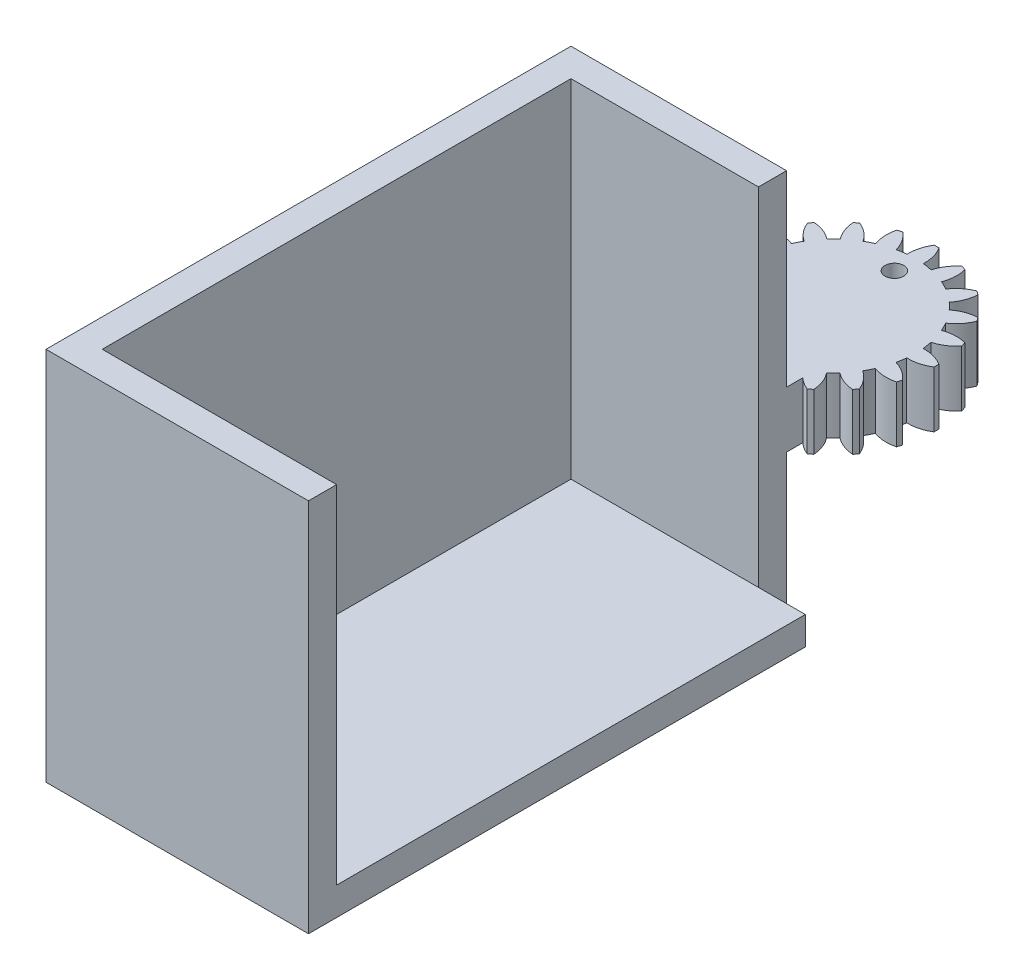
SolidWorks part; units mm, degrees
ref_plane "前视基准面" through (0, 0, 0) normal (0, 0, 1) x (1, 0, 0)
ref_plane "上视基准面" through (0, 0, 0) normal (0, 1, 0) x (1, 0, 0)
ref_plane "右视基准面" through (0, 0, 0) normal (1, 0, 0) x (0, 0, -1)
sketch "草图1" plane through (0, 0, 0) normal (0, 1, 0) x (1, 0, 0)
  line L0 (-5, 0) -> (5, 0) construction
  line L1 (5, 0) -> (5, -13)
  line L2 (-5, 0) -> (-5, -10)
  line L3 (-5, -10) -> (-18, -10)
  line L4 (-18, -10) -> (-18, -66)
  line L5 (-18, -66) -> (10, -66)
  line L6 (10, -66) -> (10, -63)
  line L7 (10, -63) -> (-15, -63)
  line L8 (-15, -63) -> (-15, -13)
  line L9 (-15, -13) -> (5, -13)
  arc A0 (5, 0) -> (-5, 0) centre (0, 0) ccw
  arc A1 (-5, 0) -> (5, 0) centre (0, 0) ccw construction
  dimension "D1" = 10
  dimension "D2" = 3
  dimension "D3" = 3
  dimension "D4" = 3
  dimension "D5" = 10
  dimension "D6" = 10
  dimension "D7" = 25
  dimension "D8" = 50
extrude "凸台-拉伸1" add sketch "草图1" against normal blind 6
sketch "草图2" plane through (0, 0, 0) normal (0, 1, 0) x (1, 0, 0)
  line L0 (-15, -13) -> (5, -13) construction
  line L1 (-15, -63) -> (-15, -13) construction
  line L2 (10, -63) -> (-15, -63) construction
  line L3 (10, -66) -> (10, -63) construction
  line L4 (-18, -66) -> (10, -66) construction
  line L5 (-18, -10) -> (-18, -66) construction
  line L6 (-15, -13) -> (5, -13)
  line L7 (-15, -63) -> (-15, -13)
  line L8 (10, -63) -> (-15, -63)
  line L9 (10, -66) -> (10, -63)
  line L10 (-18, -66) -> (10, -66)
  line L11 (-18, -10) -> (-18, -66)
  line L12 (-18, -10) -> (5, -10)
  line L13 (5, -13) -> (5, 0) construction
  line L14 (5, -10) -> (5, -13)
extrude "凸台-拉伸2" add sketch "草图2" along normal mid plane 40
sketch "草图3" plane through (0, -20, 0) normal (0, -1, 0) x (1, 0, 0)
  line L1 (-15, 13) -> (10, 13)
  line L2 (-15, 13) -> (-15, 63)
  line L3 (-15, 63) -> (10, 63)
  line L4 (10, 13) -> (10, 63)
extrude "凸台-拉伸3" add sketch "草图3" against normal blind 3
sketch "草图4" plane through (0, -6, 0) normal (0, -1, 0) x (1, 0, 0)
  arc A80 (0.8607, 8.7066) -> (0.2434, 10.9973) centre (-3.1365, 8.858) ccw
  arc A81 (0.2434, 10.9973) -> (-0.2736, 10.9966) centre (0, 0) ccw
  arc A82 (-0.2736, 10.9966) -> (-0.8846, 8.7042) centre (3.1121, 8.8666) ccw
  arc A83 (-0.8846, 8.7042) -> (-1.8719, 8.5464) centre (0, 0) ccw
  arc A84 (-1.8719, 8.5464) -> (-3.1668, 10.5343) centre (-5.7202, 7.4553) ccw
  arc A85 (-3.1668, 10.5343) -> (-3.6584, 10.3738) centre (0, 0) ccw
  arc A86 (-3.6584, 10.3738) -> (-3.531, 8.0048) centre (0.2198, 9.3944) ccw
  arc A87 (-3.531, 8.0048) -> (-4.4213, 7.5497) centre (0, 0) ccw
  arc A88 (-4.4213, 7.5497) -> (-6.2671, 9.0401) centre (-7.7441, 5.3227) ccw
  arc A89 (-6.2671, 9.0401) -> (-6.685, 8.7356) centre (0, 0) ccw
  arc A90 (-6.685, 8.7356) -> (-5.8318, 6.5219) centre (-2.6939, 9.0025) ccw
  arc A91 (-5.8318, 6.5219) -> (-6.5379, 5.8139) centre (0, 0) ccw
  arc A92 (-6.5379, 5.8139) -> (-8.7539, 6.661) centre (-9.0099, 2.6692) ccw
  arc A93 (-8.7539, 6.661) -> (-9.0573, 6.2423) centre (0, 0) ccw
  arc A94 (-9.0573, 6.2423) -> (-7.5618, 4.4005) centre (-5.344, 7.7294) ccw
  arc A95 (-7.5618, 4.4005) -> (-8.0145, 3.509) centre (0, 0) ccw
  arc A96 (-8.0145, 3.509) -> (-10.3838, 3.6299) centre (-9.3937, -0.2457) ccw
  arc A97 (-10.3838, 3.6299) -> (-10.5429, 3.1379) centre (0, 0) ccw
  arc A98 (-10.5429, 3.1379) -> (-8.5515, 1.8484) centre (-7.471, 5.6997) ccw
  arc A99 (-8.5515, 1.8484) -> (-8.7066, 0.8607) centre (0, 0) ccw
  arc A100 (-8.7066, 0.8607) -> (-10.9973, 0.2434) centre (-8.858, -3.1365) ccw
  arc A101 (-10.9973, 0.2434) -> (-10.9966, -0.2736) centre (0, 0) ccw
  arc A102 (-10.9966, -0.2736) -> (-8.7042, -0.8846) centre (-8.8666, 3.1121) ccw
  arc A103 (-8.7042, -0.8846) -> (-8.5464, -1.8719) centre (0, 0) ccw
  arc A104 (-8.5464, -1.8719) -> (-10.5343, -3.1668) centre (-7.4553, -5.7202) ccw
  arc A105 (-10.5343, -3.1668) -> (-10.3738, -3.6584) centre (0, 0) ccw
  arc A106 (-10.3738, -3.6584) -> (-8.0048, -3.531) centre (-9.3944, 0.2198) ccw
  arc A107 (-8.0048, -3.531) -> (-7.5497, -4.4213) centre (0, 0) ccw
  arc A108 (-7.5497, -4.4213) -> (-9.0401, -6.2671) centre (-5.3227, -7.7441) ccw
  arc A109 (-9.0401, -6.2671) -> (-8.7356, -6.685) centre (0, 0) ccw
  arc A110 (-8.7356, -6.685) -> (-6.5219, -5.8318) centre (-9.0025, -2.6939) ccw
  arc A111 (-6.5219, -5.8318) -> (-5.8139, -6.5379) centre (0, 0) ccw
  arc A112 (-5.8139, -6.5379) -> (-6.661, -8.7539) centre (-2.6692, -9.0099) ccw
  arc A113 (-6.661, -8.7539) -> (-6.2423, -9.0573) centre (0, 0) ccw
  arc A114 (-6.2423, -9.0573) -> (-4.4005, -7.5618) centre (-7.7294, -5.344) ccw
  arc A115 (-4.4005, -7.5618) -> (-3.509, -8.0145) centre (0, 0) ccw
  arc A116 (-3.509, -8.0145) -> (-3.6299, -10.3838) centre (0.2457, -9.3937) ccw
  arc A117 (-3.6299, -10.3838) -> (-3.1379, -10.5429) centre (0, 0) ccw
  arc A118 (-3.1379, -10.5429) -> (-1.8484, -8.5515) centre (-5.6997, -7.471) ccw
  arc A119 (-1.8484, -8.5515) -> (-0.8607, -8.7066) centre (0, 0) ccw
  arc A120 (-0.8607, -8.7066) -> (-0.2434, -10.9973) centre (3.1365, -8.858) ccw
  arc A121 (-0.2434, -10.9973) -> (0.2736, -10.9966) centre (0, 0) ccw
  arc A122 (0.2736, -10.9966) -> (0.8846, -8.7042) centre (-3.1121, -8.8666) ccw
  arc A123 (0.8846, -8.7042) -> (1.8719, -8.5464) centre (0, 0) ccw
  arc A124 (1.8719, -8.5464) -> (3.1668, -10.5343) centre (5.7202, -7.4553) ccw
  arc A125 (3.1668, -10.5343) -> (3.6584, -10.3738) centre (0, 0) ccw
  arc A126 (3.6584, -10.3738) -> (3.531, -8.0048) centre (-0.2198, -9.3944) ccw
  arc A127 (3.531, -8.0048) -> (4.4213, -7.5497) centre (0, 0) ccw
  arc A128 (4.4213, -7.5497) -> (6.2671, -9.0401) centre (7.7441, -5.3227) ccw
  arc A129 (6.2671, -9.0401) -> (6.685, -8.7356) centre (0, 0) ccw
  arc A130 (6.685, -8.7356) -> (5.8318, -6.5219) centre (2.6939, -9.0025) ccw
  arc A131 (5.8318, -6.5219) -> (6.5379, -5.8139) centre (0, 0) ccw
  arc A132 (6.5379, -5.8139) -> (8.7539, -6.661) centre (9.0099, -2.6692) ccw
  arc A133 (8.7539, -6.661) -> (9.0573, -6.2423) centre (0, 0) ccw
  arc A134 (9.0573, -6.2423) -> (7.5618, -4.4005) centre (5.344, -7.7294) ccw
  arc A135 (7.5618, -4.4005) -> (8.0145, -3.509) centre (0, 0) ccw
  arc A136 (8.0145, -3.509) -> (10.3838, -3.6299) centre (9.3937, 0.2457) ccw
  arc A137 (10.3838, -3.6299) -> (10.5429, -3.1379) centre (0, 0) ccw
  arc A138 (10.5429, -3.1379) -> (8.5515, -1.8484) centre (7.471, -5.6997) ccw
  arc A139 (8.5515, -1.8484) -> (8.7066, -0.8607) centre (0, 0) ccw
  arc A140 (8.7066, -0.8607) -> (10.9973, -0.2434) centre (8.858, 3.1365) ccw
  arc A141 (10.9973, -0.2434) -> (10.9966, 0.2736) centre (0, 0) ccw
  arc A142 (10.9966, 0.2736) -> (8.7042, 0.8846) centre (8.8666, -3.1121) ccw
  arc A143 (8.7042, 0.8846) -> (8.5464, 1.8719) centre (0, 0) ccw
  arc A144 (8.5464, 1.8719) -> (10.5343, 3.1668) centre (7.4553, 5.7202) ccw
  arc A145 (10.5343, 3.1668) -> (10.3738, 3.6584) centre (0, 0) ccw
  arc A146 (10.3738, 3.6584) -> (8.0048, 3.531) centre (9.3944, -0.2198) ccw
  arc A147 (8.0048, 3.531) -> (7.5497, 4.4213) centre (0, 0) ccw
  arc A148 (7.5497, 4.4213) -> (9.0401, 6.2671) centre (5.3227, 7.7441) ccw
  arc A149 (9.0401, 6.2671) -> (8.7356, 6.685) centre (0, 0) ccw
  arc A150 (8.7356, 6.685) -> (6.5219, 5.8318) centre (9.0025, 2.6939) ccw
  arc A151 (6.5219, 5.8318) -> (5.8139, 6.5379) centre (0, 0) ccw
  arc A152 (5.8139, 6.5379) -> (6.661, 8.7539) centre (2.6692, 9.0099) ccw
  arc A153 (6.661, 8.7539) -> (6.2423, 9.0573) centre (0, 0) ccw
  arc A154 (6.2423, 9.0573) -> (4.4005, 7.5618) centre (7.7294, 5.344) ccw
  arc A155 (4.4005, 7.5618) -> (3.509, 8.0145) centre (0, 0) ccw
  arc A156 (3.509, 8.0145) -> (3.6299, 10.3838) centre (-0.2457, 9.3937) ccw
  arc A157 (3.6299, 10.3838) -> (3.1379, 10.5429) centre (0, 0) ccw
  arc A158 (3.1379, 10.5429) -> (1.8484, 8.5515) centre (5.6997, 7.471) ccw
  arc A159 (1.8484, 8.5515) -> (0.8607, 8.7066) centre (0, 0) ccw
  arc A160 (0.8607, 8.7066) -> (0.2434, 10.9973) centre (-3.1365, 8.858) ccw
  arc A161 (0.2434, 10.9973) -> (-0.2736, 10.9966) centre (0, 0) ccw
  arc A162 (-0.2736, 10.9966) -> (-0.8846, 8.7042) centre (3.1121, 8.8666) ccw
  arc A163 (-0.8846, 8.7042) -> (-1.8719, 8.5464) centre (0, 0) ccw
  arc A164 (-1.8719, 8.5464) -> (-3.1668, 10.5343) centre (-5.7202, 7.4553) ccw
  arc A165 (-3.1668, 10.5343) -> (-3.6584, 10.3738) centre (0, 0) ccw
  arc A166 (-3.6584, 10.3738) -> (-3.531, 8.0048) centre (0.2198, 9.3944) ccw
  arc A167 (-3.531, 8.0048) -> (-4.4213, 7.5497) centre (0, 0) ccw
  arc A168 (-4.4213, 7.5497) -> (-6.2671, 9.0401) centre (-7.7441, 5.3227) ccw
  arc A169 (-6.2671, 9.0401) -> (-6.685, 8.7356) centre (0, 0) ccw
  arc A170 (-6.685, 8.7356) -> (-5.8318, 6.5219) centre (-2.6939, 9.0025) ccw
  arc A171 (-5.8318, 6.5219) -> (-6.5379, 5.8139) centre (0, 0) ccw
  arc A172 (-6.5379, 5.8139) -> (-8.7539, 6.661) centre (-9.0099, 2.6692) ccw
  arc A173 (-8.7539, 6.661) -> (-9.0573, 6.2423) centre (0, 0) ccw
  arc A174 (-9.0573, 6.2423) -> (-7.5618, 4.4005) centre (-5.344, 7.7294) ccw
  arc A175 (-7.5618, 4.4005) -> (-8.0145, 3.509) centre (0, 0) ccw
  arc A176 (-8.0145, 3.509) -> (-10.3838, 3.6299) centre (-9.3937, -0.2457) ccw
  arc A177 (-10.3838, 3.6299) -> (-10.5429, 3.1379) centre (0, 0) ccw
  arc A178 (-10.5429, 3.1379) -> (-8.5515, 1.8484) centre (-7.471, 5.6997) ccw
  arc A179 (-8.5515, 1.8484) -> (-8.7066, 0.8607) centre (0, 0) ccw
  arc A180 (-8.7066, 0.8607) -> (-10.9973, 0.2434) centre (-8.858, -3.1365) ccw
  arc A181 (-10.9973, 0.2434) -> (-10.9966, -0.2736) centre (0, 0) ccw
  arc A182 (-10.9966, -0.2736) -> (-8.7042, -0.8846) centre (-8.8666, 3.1121) ccw
  arc A183 (-8.7042, -0.8846) -> (-8.5464, -1.8719) centre (0, 0) ccw
  arc A184 (-8.5464, -1.8719) -> (-10.5343, -3.1668) centre (-7.4553, -5.7202) ccw
  arc A185 (-10.5343, -3.1668) -> (-10.3738, -3.6584) centre (0, 0) ccw
  arc A186 (-10.3738, -3.6584) -> (-8.0048, -3.531) centre (-9.3944, 0.2198) ccw
  arc A187 (-8.0048, -3.531) -> (-7.5497, -4.4213) centre (0, 0) ccw
  arc A188 (-7.5497, -4.4213) -> (-9.0401, -6.2671) centre (-5.3227, -7.7441) ccw
  arc A189 (-9.0401, -6.2671) -> (-8.7356, -6.685) centre (0, 0) ccw
  arc A190 (-8.7356, -6.685) -> (-6.5219, -5.8318) centre (-9.0025, -2.6939) ccw
  arc A191 (-6.5219, -5.8318) -> (-5.8139, -6.5379) centre (0, 0) ccw
  arc A192 (-5.8139, -6.5379) -> (-6.661, -8.7539) centre (-2.6692, -9.0099) ccw
  arc A193 (-6.661, -8.7539) -> (-6.2423, -9.0573) centre (0, 0) ccw
  arc A194 (-6.2423, -9.0573) -> (-4.4005, -7.5618) centre (-7.7294, -5.344) ccw
  arc A195 (-4.4005, -7.5618) -> (-3.509, -8.0145) centre (0, 0) ccw
  arc A196 (-3.509, -8.0145) -> (-3.6299, -10.3838) centre (0.2457, -9.3937) ccw
  arc A197 (-3.6299, -10.3838) -> (-3.1379, -10.5429) centre (0, 0) ccw
  arc A198 (-3.1379, -10.5429) -> (-1.8484, -8.5515) centre (-5.6997, -7.471) ccw
  arc A199 (-1.8484, -8.5515) -> (-0.8607, -8.7066) centre (0, 0) ccw
  arc A200 (-0.8607, -8.7066) -> (-0.2434, -10.9973) centre (3.1365, -8.858) ccw
  arc A201 (-0.2434, -10.9973) -> (0.2736, -10.9966) centre (0, 0) ccw
  arc A202 (0.2736, -10.9966) -> (0.8846, -8.7042) centre (-3.1121, -8.8666) ccw
  arc A203 (0.8846, -8.7042) -> (1.8719, -8.5464) centre (0, 0) ccw
  arc A204 (1.8719, -8.5464) -> (3.1668, -10.5343) centre (5.7202, -7.4553) ccw
  arc A205 (3.1668, -10.5343) -> (3.6584, -10.3738) centre (0, 0) ccw
  arc A206 (3.6584, -10.3738) -> (3.531, -8.0048) centre (-0.2198, -9.3944) ccw
  arc A207 (3.531, -8.0048) -> (4.4213, -7.5497) centre (0, 0) ccw
  arc A208 (4.4213, -7.5497) -> (6.2671, -9.0401) centre (7.7441, -5.3227) ccw
  arc A209 (6.2671, -9.0401) -> (6.685, -8.7356) centre (0, 0) ccw
  arc A210 (6.685, -8.7356) -> (5.8318, -6.5219) centre (2.6939, -9.0025) ccw
  arc A211 (5.8318, -6.5219) -> (6.5379, -5.8139) centre (0, 0) ccw
  arc A212 (6.5379, -5.8139) -> (8.7539, -6.661) centre (9.0099, -2.6692) ccw
  arc A213 (8.7539, -6.661) -> (9.0573, -6.2423) centre (0, 0) ccw
  arc A214 (9.0573, -6.2423) -> (7.5618, -4.4005) centre (5.344, -7.7294) ccw
  arc A215 (7.5618, -4.4005) -> (8.0145, -3.509) centre (0, 0) ccw
  arc A216 (8.0145, -3.509) -> (10.3838, -3.6299) centre (9.3937, 0.2457) ccw
  arc A217 (10.3838, -3.6299) -> (10.5429, -3.1379) centre (0, 0) ccw
  arc A218 (10.5429, -3.1379) -> (8.5515, -1.8484) centre (7.471, -5.6997) ccw
  arc A219 (8.5515, -1.8484) -> (8.7066, -0.8607) centre (0, 0) ccw
  arc A220 (8.7066, -0.8607) -> (10.9973, -0.2434) centre (8.858, 3.1365) ccw
  arc A221 (10.9973, -0.2434) -> (10.9966, 0.2736) centre (0, 0) ccw
  arc A222 (10.9966, 0.2736) -> (8.7042, 0.8846) centre (8.8666, -3.1121) ccw
  arc A223 (8.7042, 0.8846) -> (8.5464, 1.8719) centre (0, 0) ccw
  arc A224 (8.5464, 1.8719) -> (10.5343, 3.1668) centre (7.4553, 5.7202) ccw
  arc A225 (10.5343, 3.1668) -> (10.3738, 3.6584) centre (0, 0) ccw
  arc A226 (10.3738, 3.6584) -> (8.0048, 3.531) centre (9.3944, -0.2198) ccw
  arc A227 (8.0048, 3.531) -> (7.5497, 4.4213) centre (0, 0) ccw
  arc A228 (7.5497, 4.4213) -> (9.0401, 6.2671) centre (5.3227, 7.7441) ccw
  arc A229 (9.0401, 6.2671) -> (8.7356, 6.685) centre (0, 0) ccw
  arc A230 (8.7356, 6.685) -> (6.5219, 5.8318) centre (9.0025, 2.6939) ccw
  arc A231 (6.5219, 5.8318) -> (5.8139, 6.5379) centre (0, 0) ccw
  arc A232 (5.8139, 6.5379) -> (6.661, 8.7539) centre (2.6692, 9.0099) ccw
  arc A233 (6.661, 8.7539) -> (6.2423, 9.0573) centre (0, 0) ccw
  arc A234 (6.2423, 9.0573) -> (4.4005, 7.5618) centre (7.7294, 5.344) ccw
  arc A235 (4.4005, 7.5618) -> (3.509, 8.0145) centre (0, 0) ccw
  arc A236 (3.509, 8.0145) -> (3.6299, 10.3838) centre (-0.2457, 9.3937) ccw
  arc A237 (3.6299, 10.3838) -> (3.1379, 10.5429) centre (0, 0) ccw
  arc A238 (3.1379, 10.5429) -> (1.8484, 8.5515) centre (5.6997, 7.471) ccw
  arc A239 (1.8484, 8.5515) -> (0.8607, 8.7066) centre (0, 0) ccw
  point P0 (0, 0)
  dimension "D1" = 0
extrude "凸台-拉伸4" add sketch "草图4" against normal blind 6
sketch "草图5" plane through (0, -6, 0) normal (0, -1, 0) x (1, 0, 0)
  line L0 (0, -6.5) -> (0, 6.5) construction
  circle A0 centre (0, 6.5) radius 1
  circle A1 centre (0, -6.5) radius 1
  point P4 (0, 0)
  dimension "D2" = 2
  dimension "D3" = 2
  dimension "D1" = 13
extrude "切除-拉伸1" cut sketch "草图5" against normal through all
